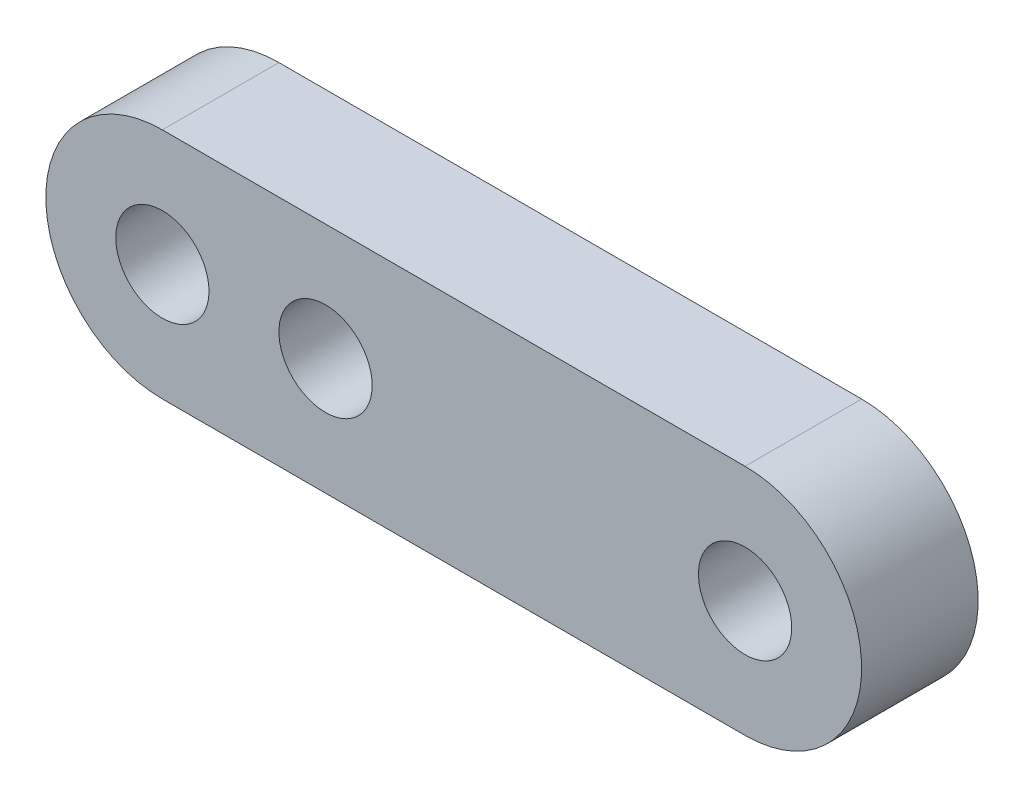
SolidWorks part; units mm, degrees
ref_plane "Front Plane" through (0, 0, 0) normal (0, 0, 1) x (1, 0, 0)
ref_plane "Top Plane" through (0, 0, 0) normal (0, 1, 0) x (1, 0, 0)
ref_plane "Right Plane" through (0, 0, 0) normal (1, 0, 0) x (0, 0, -1)
sketch "Sketch1" plane through (0, 0, 0) normal (0, 0, 1) x (1, 0, 0)
  line L1 (-15, 5) -> (10, 5)
  line L3 (-15, -5) -> (10, -5)
  arc A0 (10, -5) -> (10, 5) centre (10, 0) ccw
  arc A1 (-15, 5) -> (-15, -5) centre (-15, 0) ccw
  circle A4 centre (10, 0) radius 2
  circle A5 centre (-15, 0) radius 2
  circle A6 centre (-8, 0) radius 2
  point P0 (0, 0)
  point P11 (0, 0)
  point P12 (-54.6268, 15.7047)
  dimension "D3" = 4
  dimension "D1" = 10
  dimension "D2" = 25
  dimension "D4" = 7
extrude "Boss-Extrude2" add sketch "Sketch1" along normal blind 5
